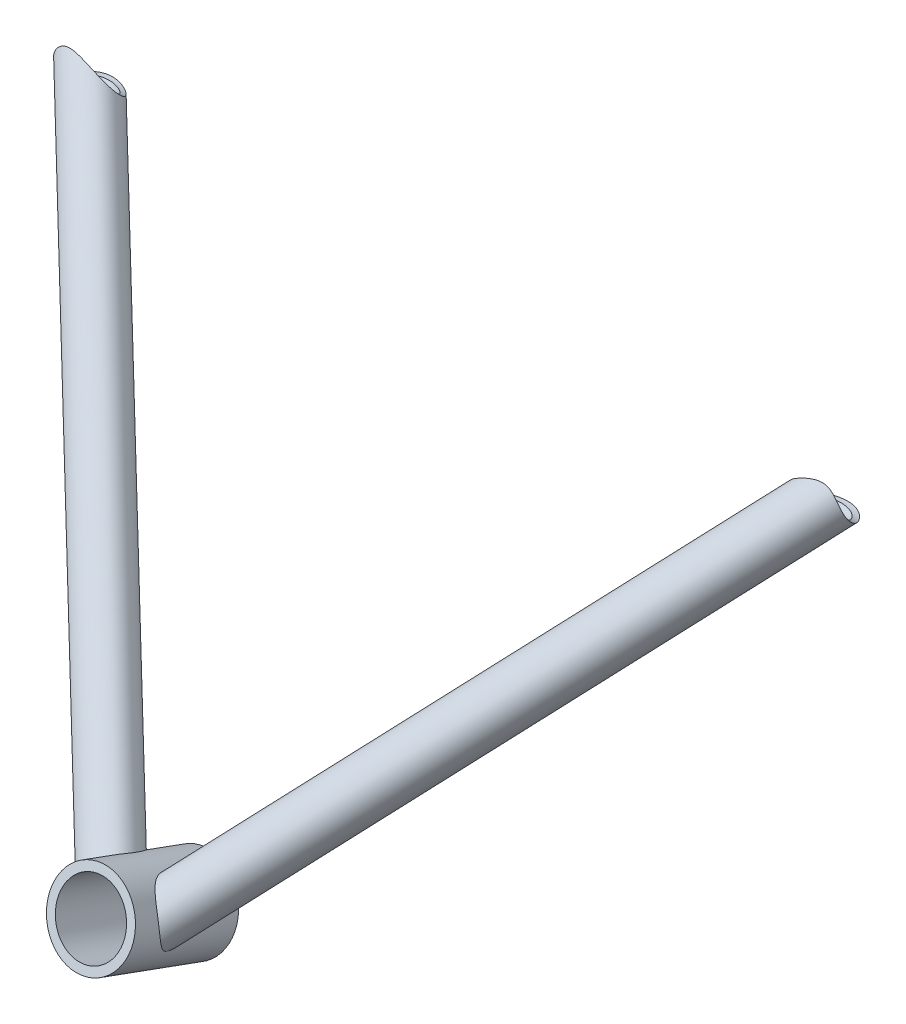
SolidWorks part; units mm, degrees
material "AISI 4130 Steel, normalized at 870C"
ref_plane "Front Plane" through (0, 0, 0) normal (0, 0, 1) x (1, 0, 0)
ref_plane "Top Plane" through (0, 0, 0) normal (0, 1, 0) x (1, 0, 0)
ref_plane "Right Plane" through (0, 0, 0) normal (1, 0, 0) x (0, 0, -1)
sketch "Sketch3" plane through (0, 0, 0) normal (0, 1, 0) x (1, 0, 0)
  line L0 (-5.08, -6.35) -> (5.08, -6.35) construction
  line L2 (0, -88.2205) -> (0, 88.2205) construction
  line L3 (5.08, 0) -> (-5.08, 0) construction
  dimension "D1" = 5.08
  dimension "D2" = 10.16
  dimension "D3" = 6.35
  dimension "D4" = 10.16
  dimension "D5" = 5.08
ref_plane "Plane1" through (0, 3.1441, 3.6169) normal (0, 0.6561, 0.7547) x (1, 0, 0)
ref_plane "Plane3" through (0, 0, 0) normal (0, 0.342, 0.9397) x (-1, 0, 0)
sketch "Sketch1" plane through (0, 0, 0) normal (0, 0.342, 0.9397) x (1, 0, 0)
  circle A0 centre (0, 0) radius 15.875
  dimension "D1" = 31.75
extrude "Boss-Extrude1" add sketch "Sketch1" along normal mid plane 41.402 contours A0
sketch "Sketch4" plane through (0, 3.1441, 3.6169) normal (0, 0.6561, 0.7547) x (1, 0, 0)
  line L0 (-5.08, -4.166) -> (-143.484, 193.4954)
  line L2 (0, -90.5202) -> (0, 90.5202) construction
  dimension "D2" = 35
  dimension "D3" = 241.3
sweep "Sweep1" add path "Sketch4" circular profile diameter 19.05 parameters "D3"=19.05
sketch "Sketch15" plane through (0, 3.1441, 3.6169) normal (0, 0.6561, 0.7547) x (1, 0, 0)
  line L0 (5.08, -4.166) -> (143.484, 193.4954)
  line L1 (0, -90.5202) -> (0, 90.5202) construction
  dimension "D1" = 241.3
  dimension "D2" = 35
sweep "Sweep2" add path "Sketch15" circular profile diameter 19.05 parameters "D3"=19.05
sketch "Sketch36" plane through (-138.1179, 148.8686, -129.4095) normal (-0.5736, 0.6182, -0.5374) x (0.8191, 0.4394, -0.3687)
  circle A0 centre (-6.5024, -4.8578) radius 7.9375
  dimension "D1" = 15.875
extrude "Cut-Extrude2" cut sketch "Sketch36" against normal up to surface (251.5099 mm away)
sketch "Sketch37" plane through (138.1179, 148.8686, -129.4095) normal (0.5736, 0.6182, -0.5374) x (0.8191, -0.4394, 0.3687)
  circle A0 centre (6.5024, -4.8578) radius 7.9375
  dimension "D1" = 15.875
extrude "Cut-Extrude3" cut sketch "Sketch37" against normal up to surface (226.8376 mm away)
sketch "Sketch77" plane through (0, 7.0802, 19.4526) normal (0, 0.342, 0.9397) x (1, 0, 0)
  circle A1 centre (0, 0) radius 15.875
extrude "Boss-Extrude2" add sketch "Sketch77" against normal up to surface (41.402 mm away) up to face at (0, -21.9978, -14.023)
sketch "Sketch2" plane through (0, -7.0802, -19.4526) normal (0, -0.342, -0.9397) x (-1, 0, 0)
  circle A0 centre (0, 0) radius 12.7
  dimension "D1" = 25.4
extrude "Cut-Extrude1" cut sketch "Sketch2" against normal up to next
ref_plane "Plane2" through (0, 0, -127) normal (0, 0, 1) x (1, 0, 0)
sketch "Sketch40" plane through (-106.934, 0, -127) normal (0, 0, 1) x (1, 0, 0)
  line L2 (106.934, -85.9333) -> (106.934, 85.9333) construction
  line L3 (100.2024, 162.3048) -> (-63.6638, 149.8608)
  line L4 (113.6656, 162.3048) -> (277.5318, 149.8608)
  arc A0 (100.2024, 162.3048) -> (113.6656, 162.3048) centre (106.934, 73.66) cw
  point P0 (106.934, 162.56)
  point P7 (106.934, 162.56)
  dimension "D1" = 164.338
  dimension "D3" = 88.9
  dimension "D2" = 164.338
  dimension "D4" = 4.75
ref_plane "Plane4" through (170.5978, 149.8608, -127) normal (-0.9971, 0.0757, 0) x (0, 0, 1)
sketch "Sketch83" plane through (170.5978, 149.8608, -127) normal (-0.9971, 0.0757, 0) x (0, 0, 1)
  circle A0 centre (0, -0.2552) radius 12.7
  dimension "D1" = 25.4
sweep "Cut-Sweep1" cut profiles "Sketch83" path "Sketch40"
